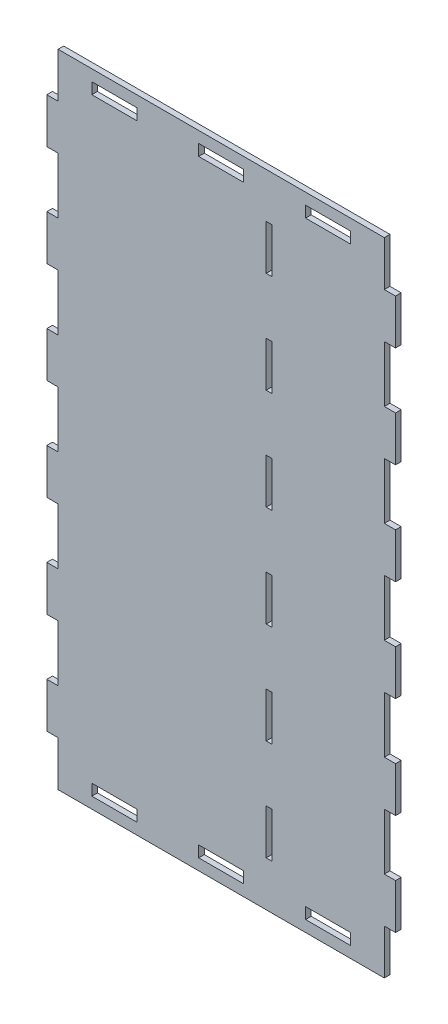
SolidWorks part; units mm, degrees
material "Mahogany"
ref_plane "Front" through (0, 0, 0) normal (0, 0, 1) x (1, 0, 0)
ref_plane "Top" through (0, 0, 0) normal (0, 1, 0) x (1, 0, 0)
ref_plane "Right" through (0, 0, 0) normal (1, 0, 0) x (0, 0, -1)
sketch "Sketch1" plane through (0, 0, 0) normal (0, 0, 1) x (1, 0, 0)
  line L0 (-72.5, -137.5) -> (-72.5, 137.5) construction
  line L1 (-77.5, -142.5) -> (77.5, -142.5) construction
  line L2 (-77.5, -142.5) -> (-77.5, 142.5) construction
  line L3 (-77.5, 142.5) -> (77.5, 142.5) construction
  line L4 (77.5, -142.5) -> (77.5, 142.5) construction
  line L5 (-77.5, -142.5) -> (77.5, 142.5) construction
  line L6 (-77.5, 142.5) -> (77.5, -142.5) construction
  line L7 (-72.5, 137.5) -> (72.5, 137.5) construction
  line L8 (72.5, -137.5) -> (72.5, 137.5) construction
  line L9 (-72.5, -137.5) -> (72.5, -137.5) construction
  line L10 (-67.5, -132.5) -> (-67.5, 132.5) construction
  line L11 (-67.5, 132.5) -> (67.5, 132.5) construction
  line L12 (67.5, -132.5) -> (67.5, 132.5) construction
  line L13 (-67.5, -132.5) -> (67.5, -132.5) construction
  line L14 (21.8613, 0) -> (-22.4881, 0) construction
  line L15 (-57.5, 137.5) -> (-37.5, 137.5)
  line L16 (-57.5, 137.5) -> (-57.5, 132.5)
  line L17 (-57.5, 132.5) -> (-37.5, 132.5)
  line L18 (-37.5, 137.5) -> (-37.5, 132.5)
  line L19 (-57.5, 137.5) -> (-37.5, 132.5) construction
  line L20 (-57.5, 132.5) -> (-37.5, 137.5) construction
  line L21 (-72.5, 122.5) -> (-77.5, 122.5)
  line L22 (-72.5, 122.5) -> (-72.5, 102.5) construction
  line L23 (-72.5, 102.5) -> (-77.5, 102.5)
  line L24 (-77.5, 122.5) -> (-77.5, 102.5)
  line L25 (-72.5, 122.5) -> (-77.5, 102.5) construction
  line L26 (-72.5, 102.5) -> (-77.5, 122.5) construction
  line L27 (0, 24.0458) -> (0, -30.0183) construction
  line L28 (-57.5, -132.5) -> (-37.5, -132.5)
  line L29 (-37.5, -137.5) -> (-37.5, -132.5)
  line L30 (-57.5, -137.5) -> (-37.5, -137.5)
  line L31 (-57.5, -137.5) -> (-57.5, -132.5)
  line L32 (-10, 137.5) -> (-10, 132.5)
  line L33 (-10, 137.5) -> (10, 137.5)
  line L34 (10, 137.5) -> (10, 132.5)
  line L35 (-10, 132.5) -> (10, 132.5)
  line L36 (-10, -132.5) -> (10, -132.5)
  line L37 (10, -137.5) -> (10, -132.5)
  line L38 (-10, -137.5) -> (10, -137.5)
  line L39 (-10, -137.5) -> (-10, -132.5)
  line L40 (37.5, 137.5) -> (37.5, 132.5)
  line L41 (37.5, 137.5) -> (57.5, 137.5)
  line L42 (57.5, 137.5) -> (57.5, 132.5)
  line L43 (37.5, 132.5) -> (57.5, 132.5)
  line L44 (37.5, -132.5) -> (57.5, -132.5)
  line L45 (57.5, -137.5) -> (57.5, -132.5)
  line L46 (37.5, -137.5) -> (57.5, -137.5)
  line L47 (37.5, -137.5) -> (37.5, -132.5)
  line L48 (72.5, 102.5) -> (77.5, 102.5)
  line L49 (77.5, 122.5) -> (77.5, 102.5)
  line L50 (72.5, 122.5) -> (77.5, 122.5)
  line L51 (-72.5, 77.5) -> (-77.5, 77.5)
  line L52 (-77.5, 77.5) -> (-77.5, 57.5)
  line L53 (-72.5, 57.5) -> (-77.5, 57.5)
  line L54 (72.5, 57.5) -> (77.5, 57.5)
  line L55 (77.5, 77.5) -> (77.5, 57.5)
  line L56 (72.5, 77.5) -> (77.5, 77.5)
  line L57 (-72.5, 32.5) -> (-77.5, 32.5)
  line L58 (-77.5, 32.5) -> (-77.5, 12.5)
  line L59 (-72.5, 12.5) -> (-77.5, 12.5)
  line L60 (72.5, 12.5) -> (77.5, 12.5)
  line L61 (77.5, 32.5) -> (77.5, 12.5)
  line L62 (72.5, 32.5) -> (77.5, 32.5)
  line L63 (-72.5, -12.5) -> (-77.5, -12.5)
  line L64 (-77.5, -12.5) -> (-77.5, -32.5)
  line L65 (-72.5, -32.5) -> (-77.5, -32.5)
  line L66 (72.5, -32.5) -> (77.5, -32.5)
  line L67 (77.5, -12.5) -> (77.5, -32.5)
  line L68 (72.5, -12.5) -> (77.5, -12.5)
  line L69 (-72.5, -57.5) -> (-77.5, -57.5)
  line L70 (-77.5, -57.5) -> (-77.5, -77.5)
  line L71 (-72.5, -77.5) -> (-77.5, -77.5)
  line L72 (72.5, -77.5) -> (77.5, -77.5)
  line L73 (77.5, -57.5) -> (77.5, -77.5)
  line L74 (72.5, -57.5) -> (77.5, -57.5)
  line L75 (-72.5, -102.5) -> (-77.5, -102.5)
  line L76 (-77.5, -102.5) -> (-77.5, -122.5)
  line L77 (-72.5, -122.5) -> (-77.5, -122.5)
  line L78 (72.5, -122.5) -> (77.5, -122.5)
  line L79 (77.5, -102.5) -> (77.5, -122.5)
  line L80 (72.5, -102.5) -> (77.5, -102.5)
  line L81 (-72.5, 122.5) -> (-72.5, 142.5)
  line L82 (72.5, 122.5) -> (72.5, 142.5)
  line L83 (72.5, 142.5) -> (-72.5, 142.5)
  line L84 (72.5, 102.5) -> (72.5, 77.5)
  line L85 (-72.5, 102.5) -> (-72.5, 77.5)
  line L86 (-72.5, 57.5) -> (-72.5, 32.5)
  line L87 (-72.5, 12.5) -> (-72.5, -12.5)
  line L88 (-72.5, -32.5) -> (-72.5, -57.5)
  line L89 (-72.5, -77.5) -> (-72.5, -102.5)
  line L90 (-72.5, -122.5) -> (-72.5, -142.5)
  line L91 (72.5, 57.5) -> (72.5, 32.5)
  line L92 (72.5, 12.5) -> (72.5, -12.5)
  line L93 (72.5, -32.5) -> (72.5, -57.5)
  line L94 (72.5, -77.5) -> (72.5, -102.5)
  line L95 (72.5, -122.5) -> (72.5, -142.5)
  line L96 (72.5, -142.5) -> (-72.5, -142.5)
  line L97 (22.5, 77.5) -> (22.5, 57.5)
  line L98 (22.5, 122.5) -> (20, 122.5)
  line L99 (22.5, 122.5) -> (22.5, 102.5)
  line L100 (22.5, 102.5) -> (20, 102.5)
  line L101 (20, 122.5) -> (20, 102.5)
  line L102 (22.5, 122.5) -> (20, 102.5) construction
  line L103 (22.5, 102.5) -> (20, 122.5) construction
  line L104 (22.5, 77.5) -> (20, 77.5)
  line L105 (20, 77.5) -> (20, 57.5)
  line L106 (22.5, 57.5) -> (20, 57.5)
  line L107 (22.5, 32.5) -> (22.5, 12.5)
  line L108 (22.5, 32.5) -> (20, 32.5)
  line L109 (20, 32.5) -> (20, 12.5)
  line L110 (22.5, 12.5) -> (20, 12.5)
  line L111 (22.5, -12.5) -> (22.5, -32.5)
  line L112 (22.5, -12.5) -> (20, -12.5)
  line L113 (20, -12.5) -> (20, -32.5)
  line L114 (22.5, -32.5) -> (20, -32.5)
  line L115 (22.5, -57.5) -> (22.5, -77.5)
  line L116 (22.5, -57.5) -> (20, -57.5)
  line L117 (20, -57.5) -> (20, -77.5)
  line L118 (22.5, -77.5) -> (20, -77.5)
  line L119 (22.5, -102.5) -> (22.5, -122.5)
  line L120 (22.5, -102.5) -> (20, -102.5)
  line L121 (20, -102.5) -> (20, -122.5)
  line L122 (22.5, -122.5) -> (20, -122.5)
  point P0 (0, 0)
  point P18 (-47.5, 135)
  point P23 (-75, 112.5)
  point P100 (21.25, 112.5)
  point P101 (0, 0)
  dimension "D1" = 285
  dimension "D2" = 155
  dimension "D5" = 20
  dimension "D6" = 20
  dimension "D7" = 20
  dimension "D8" = 3
  dimension "D9" = 20
  dimension "D11" = 20
  dimension "D12" = 55
  dimension "D13" = 2.5
  dimension "D3" = 5
  dimension "D4" = 5
  dimension "D10" = 6
  dimension "D14" = 6
extrude "Boss-Extrude1" add sketch "Sketch1" along normal blind 2.5
